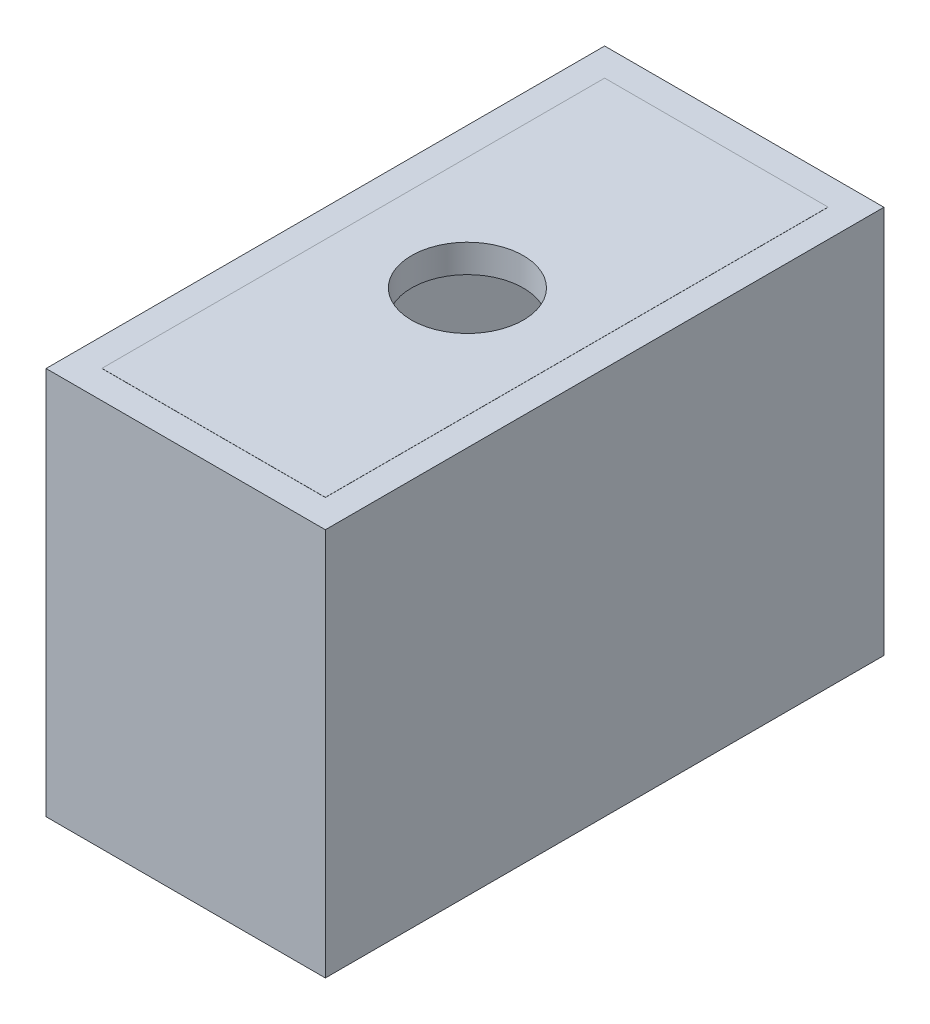
SolidWorks part; units mm, degrees
ref_plane "Front Plane" through (0, 0, 0) normal (0, 0, 1) x (1, 0, 0)
ref_plane "Top Plane" through (0, 0, 0) normal (0, 1, 0) x (1, 0, 0)
ref_plane "Right Plane" through (0, 0, 0) normal (1, 0, 0) x (0, 0, -1)
sketch "Sketch1" plane through (0, 0, 0) normal (0, 1, 0) x (1, 0, 0)
  line L1 (-25.6411, 28.0365) -> (25.1589, 28.0365)
  line L2 (-25.6411, 28.0365) -> (-25.6411, -73.5635)
  line L3 (-25.6411, -73.5635) -> (25.1589, -73.5635)
  line L4 (25.1589, 28.0365) -> (25.1589, -73.5635)
  line L5 (-20.5611, 22.9565) -> (20.0789, 22.9565)
  line L6 (-20.5611, 22.9565) -> (-20.5611, -68.4835)
  line L7 (-20.5611, -68.4835) -> (20.0789, -68.4835)
  line L8 (20.0789, 22.9565) -> (20.0789, -68.4835)
  dimension "D1" = 50.8
  dimension "D2" = 101.6
  dimension "D3" = 5.08
  dimension "D4" = 91.44
  dimension "D5" = 40.64
  dimension "D6" = 5.08
extrude "Boss-Extrude1" add sketch "Sketch1" along normal blind 70.61
sketch "Sketch2" plane through (0, 70.61, 0) normal (0, 1, 0) x (1, 0, 0)
  line L1 (-20.5611, 22.9565) -> (20.0789, 22.9565)
  line L2 (-20.5611, 22.9565) -> (-20.5611, -68.4835)
  line L3 (-20.5611, -68.4835) -> (20.0789, -68.4835)
  line L4 (20.0789, 22.9565) -> (20.0789, -68.4835)
extrude "Boss-Extrude2" add sketch "Sketch2" along normal blind 0.0254 and the other way blind 5.08
sketch "Sketch3" plane through (0, 70.6354, 0) normal (0, 1, 0) x (1, 0, 0)
  circle A0 centre (0, -22.5656) radius 10.1717
extrude "Cut-Extrude1" cut sketch "Sketch3" against normal through all
